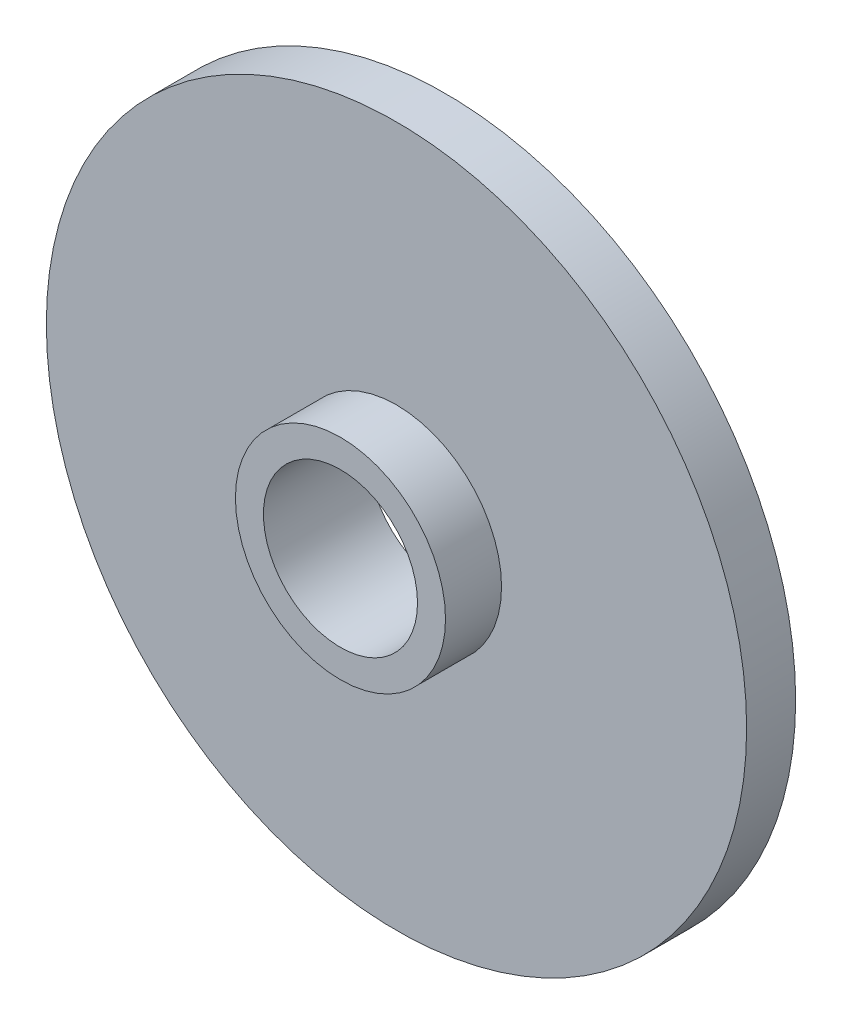
SolidWorks part; units mm, degrees
ref_plane "正面" through (0, 0, 0) normal (0, 0, 1) x (1, 0, 0)
ref_plane "平面" through (0, 0, 0) normal (0, 1, 0) x (1, 0, 0)
ref_plane "右側面" through (0, 0, 0) normal (1, 0, 0) x (0, 0, -1)
sketch "ｽｹｯﾁ1" plane through (0, 0, 0) normal (0, 0, 1) x (1, 0, 0)
  circle A0 centre (0, 0) radius 50
  dimension "D1" = 100
extrude "ﾎﾞｽ - 押し出し1" add sketch "ｽｹｯﾁ1" along normal blind 7
sketch "ｽｹｯﾁ2" plane through (0, 0, 7) normal (0, 0, 1) x (1, 0, 0)
  circle A0 centre (0, 0) radius 15
  dimension "D1" = 30
extrude "ﾎﾞｽ - 押し出し2" add sketch "ｽｹｯﾁ2" along normal blind 8
sketch "ｽｹｯﾁ3" plane through (0, 0, 15) normal (0, 0, 1) x (1, 0, 0)
  circle A0 centre (0, 0) radius 11
  dimension "D1" = 22
extrude "ｶｯﾄ - 押し出し1" cut sketch "ｽｹｯﾁ3" against normal through all
